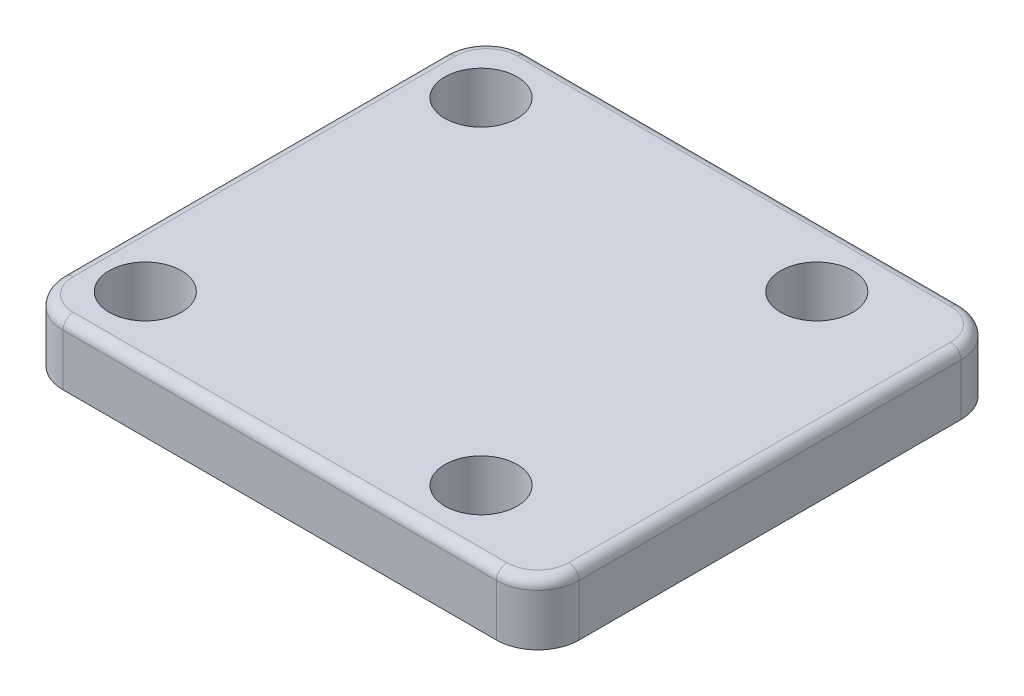
SolidWorks part; units mm, degrees
ref_plane "Front Plane" through (0, 0, 0) normal (0, 0, 1) x (1, 0, 0)
ref_plane "Top Plane" through (0, 0, 0) normal (0, 1, 0) x (1, 0, 0)
ref_plane "Right Plane" through (0, 0, 0) normal (1, 0, 0) x (0, 0, -1)
sketch "Sketch1" plane through (0, 0, 0) normal (0, 1, 0) x (1, 0, 0)
  line L1 (24, 22.5) -> (-18, 22.5)
  line L2 (28, 18.5) -> (28, -18.5)
  line L3 (24, -22.5) -> (-18, -22.5)
  line L4 (-22, 18.5) -> (-22, -18.5)
  arc A0 (-18, 22.5) -> (-22, 18.5) centre (-18, 18.5) ccw
  arc A1 (28, -18.5) -> (24, -22.5) centre (24, -18.5) cw
  arc A2 (-18, -22.5) -> (-22, -18.5) centre (-18, -18.5) cw
  arc A3 (24, 22.5) -> (28, 18.5) centre (24, 18.5) cw
  point P7 (-22, 22.5)
  point P10 (28, -22.5)
  point P15 (28, 22.5)
  dimension "D5" = 4
  dimension "D1" = 50
  dimension "D2" = 45
  dimension "D3" = 22
  dimension "D4" = 22.5
extrude "Boss-Extrude1" add sketch "Sketch1" along normal blind 6
fillet "Fillet1" radius 1 8 edges at (3, 6, -22.5) (26.8284, 6, -21.3284) (28, 6, 0) (26.8284, 6, 21.3284) (3, 6, 22.5) (-20.8284, 6, 21.3284) (-22, 6, 0) (-20.8284, 6, -21.3284)
sketch "Sketch2" plane through (0, 0, 0) normal (0, -1, 0) x (1, 0, 0)
  circle A0 centre (0, 0) radius 16
  dimension "D1" = 32
extrude "Boss-Extrude2" add sketch "Sketch2" along normal blind 2
chamfer "Chamfer1" distance 1 angle 60 1 edges at (0, -2, -16)
sketch "Sketch3" plane through (0, 6, 0) normal (0, 1, 0) x (1, 0, 0)
  line L0 (0, 0) -> (-16.2635, 16.2635) construction
  line L1 (0, 0) -> (-23, 0) construction
  circle A0 centre (0, 0) radius 23 construction
  circle A1 centre (-16.2635, 16.2635) radius 3.5
  circle A2 centre (16.2635, 16.2635) radius 3.5
  circle A3 centre (16.2635, -16.2635) radius 3.5
  circle A4 centre (-16.2635, -16.2635) radius 3.5
  point P15 (0, 0)
  dimension "D1" = 46
  dimension "D3" = 7
  dimension "D2" = 45
  dimension "D4" = 4
extrude "Cut-Extrude1" cut sketch "Sketch3" against normal through all
